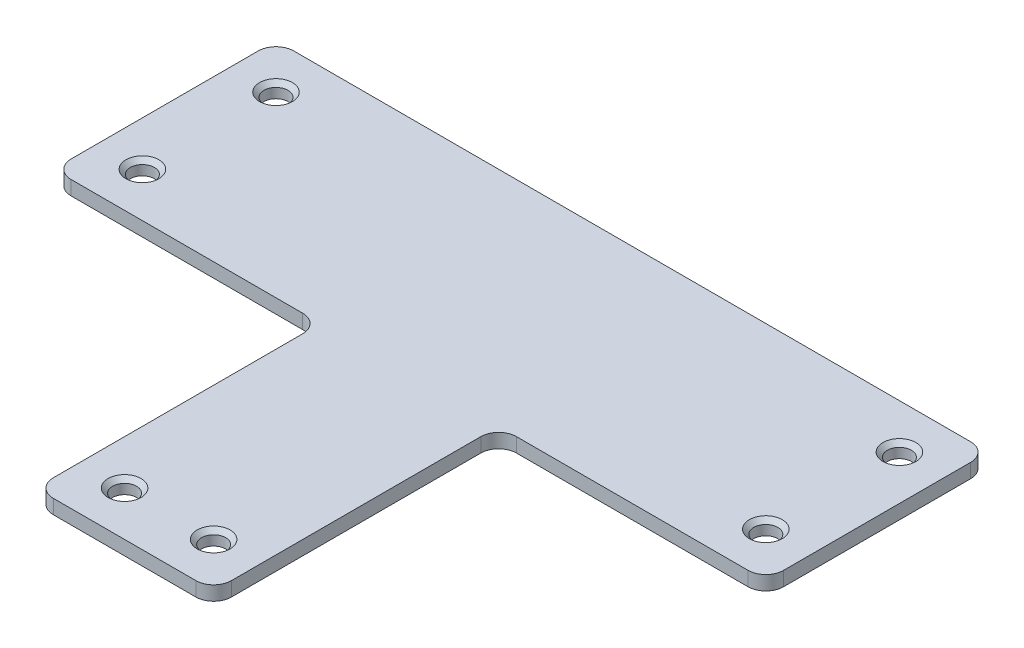
SolidWorks part; units mm, degrees
ref_plane "Front Plane" through (0, 0, 0) normal (0, 0, 1) x (1, 0, 0)
ref_plane "Top Plane" through (0, 0, 0) normal (0, 1, 0) x (1, 0, 0)
ref_plane "Right Plane" through (0, 0, 0) normal (1, 0, 0) x (0, 0, -1)
sketch "Sketch1" plane through (0, 0, 0) normal (0, 1, 0) x (1, 0, 0)
  line L1 (-40, -12.5) -> (40, -12.5)
  line L2 (-40, -12.5) -> (-40, 12.5)
  line L3 (-40, 12.5) -> (40, 12.5)
  line L4 (40, -12.5) -> (40, 12.5)
  line L5 (-40, -12.5) -> (40, 12.5) construction
  line L6 (-40, 12.5) -> (40, -12.5) construction
  point P0 (0, 0)
  dimension "D1" = 80
extrude "Boss-Extrude1" add sketch "Sketch1" along normal blind 1.6
sketch "Sketch2" plane through (0, 1.6, 0) normal (0, 1, 0) x (1, 0, 0)
  line L0 (-40, -12.5) -> (40, -12.5) construction
  line L1 (-10, -12.5) -> (10, -12.5)
  line L2 (-10, -12.5) -> (-10, -44.5)
  line L3 (-10, -44.5) -> (10, -44.5)
  line L4 (10, -12.5) -> (10, -44.5)
  line L5 (-40, 12.5) -> (-40, -12.5) construction
  line L6 (40, -12.5) -> (40, 12.5) construction
  dimension "D1" = 30
  dimension "D2" = 30
  dimension "D3" = 32
extrude "Boss-Extrude2" add sketch "Sketch2" against normal blind 1.6
sketch "Sketch3" plane through (0, 1.6, 0) normal (0, 1, 0) x (1, 0, 0)
  line L0 (40, 12.5) -> (-40, 12.5) construction
  line L1 (-40, 12.5) -> (-40, -12.5) construction
  circle A0 centre (-35, 7.5) radius 1.35
  dimension "D1" = 2.7
  dimension "D2" = 5
  dimension "D3" = 5
extrude "Cut-Extrude1" cut sketch "Sketch3" against normal blind 1.6
sketch "Sketch4" plane through (0, 1.6, 0) normal (0, 1, 0) x (1, 0, 0)
  line L0 (40, 12.5) -> (-40, 12.5) construction
  line L1 (40, -12.5) -> (40, 12.5) construction
  circle A0 centre (35, 7.5) radius 1.35
  dimension "D1" = 5
  dimension "D2" = 5
extrude "Cut-Extrude2" cut sketch "Sketch4" against normal blind 1.6
sketch "Sketch5" plane through (0, 1.6, 0) normal (0, 1, 0) x (1, 0, 0)
  line L0 (-40, -12.5) -> (-10, -12.5) construction
  line L1 (-40, 12.5) -> (-40, -12.5) construction
  circle A0 centre (-35, -7.5) radius 1.35
  dimension "D1" = 5
  dimension "D2" = 5
extrude "Cut-Extrude3" cut sketch "Sketch5" against normal blind 1.6
sketch "Sketch6" plane through (0, 1.6, 0) normal (0, 1, 0) x (1, 0, 0)
  line L0 (40, -12.5) -> (40, 12.5) construction
  line L1 (10, -12.5) -> (40, -12.5) construction
  circle A0 centre (35, -7.5) radius 1.35
  dimension "D1" = 5
  dimension "D2" = 5
extrude "Cut-Extrude4" cut sketch "Sketch6" against normal blind 1.6
sketch "Sketch7" plane through (0, 1.6, 0) normal (0, 1, 0) x (1, 0, 0)
  line L0 (-10, -44.5) -> (10, -44.5) construction
  line L1 (-10, -12.5) -> (-10, -44.5) construction
  circle A0 centre (-5, -39.5) radius 1.35
  dimension "D1" = 5
  dimension "D2" = 5
extrude "Cut-Extrude5" cut sketch "Sketch7" against normal blind 1.6
sketch "Sketch8" plane through (0, 1.6, 0) normal (0, 1, 0) x (1, 0, 0)
  line L0 (10, -44.5) -> (10, -12.5) construction
  line L1 (-10, -44.5) -> (10, -44.5) construction
  circle A0 centre (5, -39.5) radius 1.35
  dimension "D1" = 2.7
  dimension "D2" = 5
  dimension "D3" = 5
extrude "Cut-Extrude6" cut sketch "Sketch8" against normal blind 1.6
chamfer "Chamfer1" distance 0.5 angle 45 6 edges at (35, 1.6, -6.15) (35, 1.6, 8.85) (5, 1.6, 40.85) (-5, 1.6, 40.85) (-35, 1.6, 8.85) (-35, 1.6, -6.15)
fillet "Fillet1" radius 2 8 edges at (-40, 0.8, -12.5) (40, 0.8, -12.5) (40, 0.8, 12.5) (10, 0.8, 44.5) (-10, 0.8, 44.5) (-40, 0.8, 12.5)
